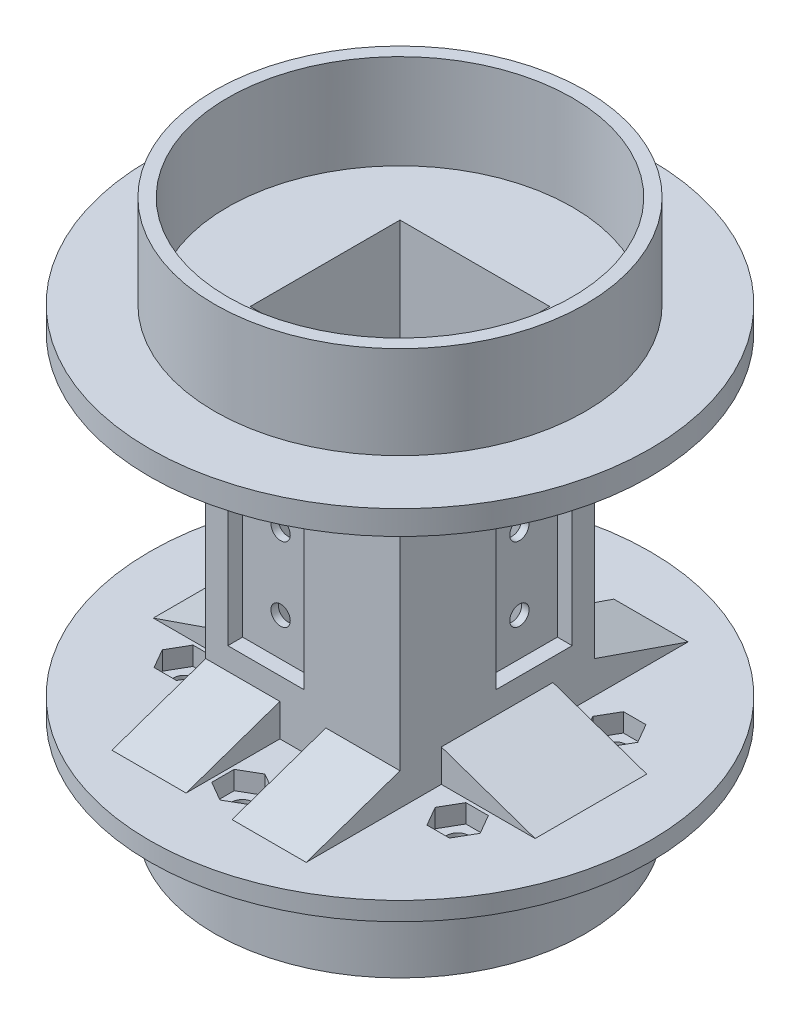
SolidWorks part; units mm, degrees
other "Markup1"
sketch "Sketch32" plane through (-67.5, -120, 67.5) normal (-0.5, 0, 0.866) x (0.866, 0, 0.5)
material "PLA"
ref_plane "Front Plane" through (0, 0, 0) normal (0, 0, 1) x (1, 0, 0)
ref_plane "Top Plane" through (0, 0, 0) normal (0, 1, 0) x (1, 0, 0)
ref_plane "Right Plane" through (0, 0, 0) normal (1, 0, 0) x (0, 0, -1)
sketch "Sketch1" plane through (0, 0, 0) normal (0, 1, 0) x (1, 0, 0)
  circle A0 centre (0, 0) radius 51.5
  circle A1 centre (0, 0) radius 46.5
  dimension "D1" = 103
  dimension "D2" = 93
extrude "Boss-Extrude1" add sketch "Sketch1" along normal blind 41
sketch "Sketch2" plane through (0, 0, 0) normal (0, -1, 0) x (1, 0, 0)
  circle A0 centre (0, 0) radius 46.5
  circle A1 centre (0, 0) radius 75
  dimension "D1" = 150
extrude "Boss-Extrude2" add sketch "Sketch2" along normal blind 5
sketch "Sketch3" plane through (0, -5, 0) normal (0, -1, 0) x (1, 0, 0)
  line L5 (-20.2, -20.2) -> (20.2, 20.2) construction
  line L6 (-20.2, 20.2) -> (20.2, -20.2) construction
  circle A0 centre (0, 0) radius 46.5
  point P0 (0, 0)
  dimension "D1" = 40.4
  dimension "D2" = 40.4
extrude "Boss-Extrude3" add sketch "Sketch3" against normal up to surface (5 mm away) up to face at (0, 0, 51.5)
sketch "Sketch4" plane through (0, 0, 0) normal (0, 1, 0) x (1, 0, 0)
  line L1 (-20.2, -20.2) -> (20.2, -20.2)
  line L2 (-20.2, -20.2) -> (-20.2, 20.2)
  line L3 (-20.2, 20.2) -> (20.2, 20.2)
  line L4 (20.2, -20.2) -> (20.2, 20.2)
  line L5 (-20.2, -20.2) -> (20.2, 20.2) construction
  line L6 (-20.2, 20.2) -> (20.2, -20.2) construction
  point P0 (0, 0)
  dimension "D1" = 40.4
  dimension "D2" = 40.4
extrude "Cut-Extrude1" cut sketch "Sketch4" against normal blind 6
sketch "Sketch5" plane through (0, -5, 0) normal (0, -1, 0) x (1, 0, 0)
  line L1 (-20.2, -20.2) -> (20.2, -20.2)
  line L2 (-20.2, -20.2) -> (-20.2, 20.2)
  line L3 (-20.2, 20.2) -> (20.2, 20.2)
  line L4 (20.2, -20.2) -> (20.2, 20.2)
  line L5 (-20.2, -20.2) -> (20.2, 20.2) construction
  line L6 (-20.2, 20.2) -> (20.2, -20.2) construction
  line L7 (-26.2, -26.2) -> (26.2, -26.2)
  line L8 (-26.2, -26.2) -> (-26.2, 26.2)
  line L9 (-26.2, 26.2) -> (26.2, 26.2)
  line L10 (26.2, -26.2) -> (26.2, 26.2)
  line L11 (-26.2, -26.2) -> (26.2, 26.2) construction
  line L12 (-26.2, 26.2) -> (26.2, -26.2) construction
  point P0 (0, 0)
  point P7 (0, 0)
  point P12 (-20.2, 0)
  point P13 (-26.2, 0)
  dimension "D1" = 6
  dimension "D2" = 6
extrude "Boss-Extrude4" add sketch "Sketch5" along normal blind 80
sketch "Sketch8" plane through (0, -85, 0) normal (0, -1, 0) x (1, 0, 0)
  line L1 (-26.2, -26.2) -> (26.2, -26.2)
  line L2 (-26.2, -26.2) -> (-26.2, 26.2)
  line L3 (-26.2, 26.2) -> (26.2, 26.2)
  line L4 (26.2, -26.2) -> (26.2, 26.2)
  line L5 (-26.2, -26.2) -> (26.2, 26.2) construction
  line L6 (-26.2, 26.2) -> (26.2, -26.2) construction
  point P0 (0, 0)
extrude "Boss-Extrude5" add sketch "Sketch8" along normal blind 5
sketch "Sketch9" plane through (0, 0, 0) normal (0, 1, 0) x (1, 0, 0)
  circle A0 centre (0, 0) radius 75
  circle A1 centre (0, 0) radius 51.5
extrude "Cut-Extrude4" cut sketch "Sketch9" against normal blind 1
sketch "Sketch10" plane through (0, -5, 0) normal (0, -1, 0) x (1, 0, 0)
  line L1 (-26.2, -26.2) -> (26.2, -26.2)
  line L2 (-26.2, -26.2) -> (-26.2, 26.2)
  line L3 (-26.2, 26.2) -> (26.2, 26.2)
  line L4 (26.2, -26.2) -> (26.2, 26.2)
  line L5 (-26.2, -26.2) -> (26.2, 26.2) construction
  line L6 (-26.2, 26.2) -> (26.2, -26.2) construction
  circle A0 centre (0, 0) radius 75
extrude "Boss-Extrude6" add sketch "Sketch10" along normal blind 1
sketch "Sketch11" plane through (0, 41, 0) normal (0, 1, 0) x (1, 0, 0)
  circle A0 centre (0, 0) radius 46.5
  circle A1 centre (0, 0) radius 51.5
extrude "Cut-Extrude5" cut sketch "Sketch11" against normal blind 13 and the other way through all
sketch "Sketch12" plane through (0, -85, 0) normal (0, 1, 0) x (1, 0, 0)
  line L1 (-20.2, -20.2) -> (20.2, -20.2)
  line L2 (-20.2, -20.2) -> (-20.2, 20.2)
  line L3 (-20.2, 20.2) -> (20.2, 20.2)
  line L4 (20.2, -20.2) -> (20.2, 20.2)
  line L5 (-20.2, -20.2) -> (20.2, 20.2) construction
  line L6 (-20.2, 20.2) -> (20.2, -20.2) construction
  point P0 (0, 0)
extrude "Cut-Extrude6" cut sketch "Sketch12" against normal blind 1
sketch "Sketch13" plane through (0, -90, 0) normal (0, -1, 0) x (1, 0, 0)
  line L1 (-26.2, -26.2) -> (26.2, -26.2)
  line L2 (-26.2, -26.2) -> (-26.2, 26.2)
  line L3 (-26.2, 26.2) -> (26.2, 26.2)
  line L4 (26.2, -26.2) -> (26.2, 26.2)
  line L5 (-26.2, -26.2) -> (26.2, 26.2) construction
  line L6 (-26.2, 26.2) -> (26.2, -26.2) construction
  point P0 (0, 0)
extrude "Boss-Extrude7" add sketch "Sketch13" along normal blind 1
sketch "Sketch6" plane through (0, 0, 26.2) normal (0, 0, 1) x (1, 0, 0)
  line L0 (-10, -6) -> (-10, -86) construction
  line L3 (26.2, -6) -> (-26.2, -6) construction
  line L4 (-20.25, -76.25) -> (0.25, -76.25)
  line L5 (-20.25, -76.25) -> (-20.25, -15.75)
  line L6 (-20.25, -15.75) -> (0.25, -15.75)
  line L7 (0.25, -76.25) -> (0.25, -15.75)
  line L8 (-20.25, -76.25) -> (0.25, -15.75) construction
  line L9 (-20.25, -15.75) -> (0.25, -76.25) construction
  line L10 (-26.2, -91) -> (-26.2, -6) construction
  point P6 (-10, -46)
  dimension "D1" = 20.5
  dimension "D2" = 60.5
  dimension "D3" = 9.75
  dimension "D4" = 5.95
extrude "Cut-Extrude2" cut sketch "Sketch6" against normal blind 4
sketch "Sketch7" plane through (0, 0, 22.2) normal (0, 0, 1) x (1, 0, 0)
  line L0 (0.25, -15.75) -> (-20.25, -15.75) construction
  circle A0 centre (-10, -26) radius 2.6
  circle A1 centre (-10, -46) radius 2.6
  circle A2 centre (-10, -66) radius 2.6
  point P10 (-10, -15.75)
  dimension "D1" = 5.2
  dimension "D2" = 5.2
  dimension "D3" = 5.2
  dimension "D4" = 10.25
  dimension "D5" = 20
  dimension "D6" = 20
  dimension "D7" = 0
extrude "Cut-Extrude3" cut sketch "Sketch7" against normal blind 2
sketch "Sketch14" plane through (-26.2, 0, 0) normal (-1, 0, 0) x (0, 0, 1)
  line L0 (26.2, -6) -> (-26.2, -6) construction
  line L1 (-0.25, -76.25) -> (20.25, -76.25)
  line L2 (-0.25, -76.25) -> (-0.25, -15.75)
  line L3 (-0.25, -15.75) -> (20.25, -15.75)
  line L4 (20.25, -76.25) -> (20.25, -15.75)
  line L5 (-0.25, -76.25) -> (20.25, -15.75) construction
  line L6 (-0.25, -15.75) -> (20.25, -76.25) construction
  line L7 (26.2, -91) -> (26.2, -6) construction
  point P0 (10, -46)
  dimension "D1" = 20.5
  dimension "D2" = 60.5
  dimension "D3" = 9.75
  dimension "D4" = 5.95
extrude "Cut-Extrude7" cut sketch "Sketch14" against normal blind 4
sketch "Sketch15" plane through (-22.2, 0, 0) normal (-1, 0, 0) x (0, 0, 1)
  line L0 (20.25, -15.75) -> (-0.25, -15.75) construction
  line L1 (-0.25, -15.75) -> (-0.25, -76.25) construction
  circle A0 centre (10, -26) radius 2.6
  circle A1 centre (10, -46) radius 2.6
  circle A2 centre (10, -66) radius 2.6
  dimension "D1" = 5.2
  dimension "D2" = 5.2
  dimension "D3" = 5.2
  dimension "D4" = 10.25
  dimension "D5" = 20
  dimension "D6" = 20
  dimension "D7" = 10.25
extrude "Cut-Extrude8" cut sketch "Sketch15" against normal blind 4
pattern_circular "CirPattern1" count 2 over 360 about axis through (0, 0, 0) along (0, 1, 0) of "Cut-Extrude2", "Cut-Extrude3"
pattern_circular "CirPattern2" count 2 over 360 about axis through (0, 0, 0) along (0, 1, 0) of "Cut-Extrude7", "Cut-Extrude8"
sketch "Sketch16" plane through (0, -1, 0) normal (0, 1, 0) x (1, 0, 0)
  circle A0 centre (0, 0) radius 75
  circle A1 centre (0, 0) radius 67.5
  dimension "D1" = 135
extrude "Cut-Extrude9" cut sketch "Sketch16" against normal blind 14
sketch "Sketch17" plane through (0, -91, 0) normal (0, -1, 0) x (1, 0, 0)
  circle A0 centre (0, 0) radius 67.5
extrude "Boss-Extrude8" add sketch "Sketch17" along normal blind 5
sketch "Sketch19" plane through (-26.2, 0, 0) normal (-1, 0, 0) x (0, 0, 1)
  line L0 (-26.2, -14.75) -> (26.2, -14.75) construction
  line L1 (-26.2, -91) -> (-26.2, -6) construction
  line L2 (26.2, -91) -> (26.2, -6) construction
  line L3 (20.25, -15.75) -> (-0.25, -15.75) construction
  line L4 (26.2, -14.75) -> (51.5, -6)
  line L5 (-67.5, -6) -> (67.5, -6) construction
  line L7 (26.2, -14.75) -> (26.2, -6)
  line L8 (26.2, -6) -> (51.5, -6)
  point P14 (51.5, -1)
  dimension "D1" = 1
extrude "Boss-Extrude9" add sketch "Sketch19" against normal up to surface (52.4 mm away) up to face at (26.2, -46, -10)
sketch "Sketch20" plane through (0, 0, 26.2) normal (0, 0, 1) x (1, 0, 0)
  line L0 (-26.2, -14.75) -> (26.2, -14.75) construction
  line L1 (-26.2, -14.75) -> (-26.2, -6) construction
  line L2 (26.2, -6) -> (26.2, -14.75) construction
  line L4 (0.25, -15.75) -> (-20.25, -15.75) construction
  line L5 (-26.2, -14.75) -> (-51.5, -6)
  line L6 (-67.5, -6) -> (67.5, -6) construction
  line L7 (-51.5, -6) -> (-26.2, -6)
  line L8 (-26.2, -6) -> (-26.2, -14.75)
  point P0 (-51.5, -1)
  dimension "D1" = 1
extrude "Boss-Extrude10" add sketch "Sketch20" against normal up to surface (52.4 mm away) up to face at (10, -46, -26.2)
sketch "Sketch21" plane through (-26.2, 0, 0) normal (-1, 0, 0) x (0, 0, 1)
  line L0 (-26.2, -14.75) -> (-51.5, -6)
  line L1 (-67.5, -6) -> (67.5, -6) construction
  line L2 (-51.5, -6) -> (-26.2, -6)
  line L3 (-26.2, -6) -> (-26.2, -14.75)
  point P0 (-51.5, -1)
extrude "Boss-Extrude11" add sketch "Sketch21" against normal up to surface (52.4 mm away) up to face at (26.2, -46, -10)
sketch "Sketch22" plane through (0, 0, -26.2) normal (0, 0, -1) x (-1, 0, 0)
  line L0 (-26.2, -14.75) -> (-51.5, -6)
  line L1 (-67.5, -6) -> (67.5, -6) construction
  line L2 (-51.5, -6) -> (-26.2, -6)
  line L3 (-26.2, -6) -> (-26.2, -14.75)
  point P0 (-51.5, -1)
extrude "Boss-Extrude12" add sketch "Sketch22" against normal up to surface (52.4 mm away) up to face at (-10, -46, 26.2)
sketch "Sketch23" plane through (26.2, 0, 0) normal (1, 0, 0) x (0, 0, -1)
  line L0 (67.5, -91) -> (-67.5, -91) construction
  line L1 (-26.2, -91) -> (-26.2, -14.75) construction
  line L2 (-51.5, -91) -> (-26.2, -82.25)
  line L3 (-26.2, -82.25) -> (-26.2, -91)
  line L4 (-26.2, -91) -> (-51.5, -91)
  point P0 (-51.5, -91)
  point P1 (-26.2, -82.25)
  point P11 (-51.5, -6)
  dimension "D1" = 8.75
sketch "Sketch24" plane through (0, 0, 26.2) normal (0, 0, 1) x (1, 0, 0)
  line L0 (-26.2, -82.25) -> (-51.5, -91)
  line L1 (67.5, -91) -> (-67.5, -91) construction
  line L2 (-51.5, -91) -> (-26.2, -91)
  line L3 (-26.2, -91) -> (-26.2, -82.25)
  point P0 (-51.5, -6)
sketch "Sketch25" plane through (-26.2, 0, 0) normal (-1, 0, 0) x (0, 0, 1)
  line L0 (-26.2, -82.25) -> (-51.5, -91)
  line L1 (67.5, -91) -> (-67.5, -91) construction
  line L2 (-51.5, -91) -> (-26.2, -91)
  line L3 (-26.2, -91) -> (-26.2, -82.25)
  point P0 (-51.5, -6)
sketch "Sketch26" plane through (0, 0, -26.2) normal (0, 0, -1) x (-1, 0, 0)
  line L0 (-26.2, -82.25) -> (-51.5, -91)
  line L1 (67.5, -91) -> (-67.5, -91) construction
  line L2 (-51.5, -91) -> (-26.2, -91)
  line L3 (-26.2, -91) -> (-26.2, -82.25)
  point P0 (-51.5, -6)
sketch "Sketch27" plane through (0, -86, 0) normal (0, 1, 0) x (1, 0, 0)
  line L0 (12.6, 22.2) -> (7.4, 22.2) construction
  line L1 (12.6, 22.2) -> (7.4, 22.2)
  line L2 (4.5, 20.2) -> (15.5, 20.2)
  line L3 (20.2, 20.2) -> (-20.2, 20.2) construction
  line L4 (-22.2, -7.4) -> (-22.2, -12.6) construction
  line L5 (-12.6, -22.2) -> (-7.4, -22.2) construction
  line L6 (22.2, 7.4) -> (22.2, 12.6) construction
  line L7 (-22.2, -7.4) -> (-22.2, -12.6)
  line L8 (-12.6, -22.2) -> (-7.4, -22.2)
  line L9 (22.2, 7.4) -> (22.2, 12.6)
  line L10 (20.2, 4.5) -> (20.2, 15.5)
  line L11 (20.2, -20.2) -> (20.2, 20.2) construction
  line L12 (-20.2, -15.5) -> (-20.2, -4.5)
  line L13 (4.5, 20.2) -> (15.5, 20.2)
  line L14 (4.5, 20.2) -> (4.5, 16.2)
  line L15 (4.5, 16.2) -> (15.5, 16.2)
  line L16 (15.5, 20.2) -> (15.5, 16.2)
  line L17 (20.2, 15.5) -> (16.2, 15.5)
  line L18 (20.2, 15.5) -> (20.2, 4.5)
  line L19 (20.2, 4.5) -> (16.2, 4.5)
  line L20 (16.2, 15.5) -> (16.2, 4.5)
  line L22 (-20.2, 20.2) -> (-20.2, -20.2) construction
  line L23 (-15.5, -20.2) -> (-4.5, -20.2)
  line L24 (-20.2, -15.5) -> (-16.2, -15.5)
  line L25 (-20.2, -15.5) -> (-20.2, -4.5)
  line L26 (-20.2, -4.5) -> (-16.2, -4.5)
  line L27 (-16.2, -15.5) -> (-16.2, -4.5)
  line L30 (-15.5, -20.2) -> (-4.5, -20.2)
  line L31 (-15.5, -20.2) -> (-15.5, -16.2)
  line L32 (-15.5, -16.2) -> (-4.5, -16.2)
  line L33 (-4.5, -20.2) -> (-4.5, -16.2)
  point P2 (22.2, 10)
  point P7 (10, 20.2)
  point P8 (10, 22.2)
  point P20 (20.2, 10)
  point P24 (-22.2, -10)
  point P27 (-20.2, -10)
  point P28 (-10, -22.2)
  point P37 (-10, -20.2)
  line M9 (20.2, -20.2) -> (20.2, 20.2)
  line M10 (20.2, 20.2) -> (-20.2, 20.2)
  line M11 (-20.2, 20.2) -> (-20.2, -20.2)
  line M12 (-20.2, -20.2) -> (20.2, -20.2)
  dimension "D1" = 11
  dimension "D2" = 11
  dimension "D3" = 4
  dimension "D4" = 4
  dimension "D5" = 11
  dimension "D6" = 4
  dimension "D7" = 11
  dimension "D8" = 4
extrude "Cut-Extrude10" cut sketch "Sketch27" against normal blind 20 contours L16 L14 L15 M10 | L17 L20 L19 M9 | L24 L27 L26 M11 | L33 L32 L31 M12
sketch "Sketch28" plane through (0, 28, 0) normal (0, 1, 0) x (1, 0, 0)
  circle A0 centre (0, 0) radius 50
  circle A1 centre (0, 0) radius 51.5
  dimension "D1" = 100
extrude "Cut-Extrude11" cut sketch "Sketch28" against normal up to surface (29 mm away) up to face at (0, -1, 51.5)
sketch "Sketch29" plane through (0, -96, 0) normal (0, -1, 0) x (1, 0, 0)
  circle A0 centre (0, 0) radius 50
  circle A1 centre (0, 0) radius 45
  dimension "D1" = 100
  dimension "D2" = 90
extrude "Boss-Extrude17" add sketch "Sketch29" along normal blind 24
sketch "Sketch30" plane through (0, -96, 0) normal (0, -1, 0) x (1, 0, 0)
  line L0 (0.25, 22.2) -> (0.25, 26.2) construction
  line L1 (-20.25, 22.2) -> (-20.25, 26.2) construction
  line L2 (0.25, 22.2) -> (0.25, 26.2)
  line L3 (-20.25, 22.2) -> (-20.25, 26.2)
  line L4 (-20.25, 22.2) -> (0.25, 22.2) construction
  line L5 (-4.5, 20.2) -> (-15.5, 20.2) construction
  line L6 (-15.75, 15.95) -> (-4.25, 15.95)
  line L7 (-15.75, 15.95) -> (-15.75, 20.45)
  line L8 (-15.75, 20.45) -> (-4.25, 20.45)
  line L9 (-4.25, 15.95) -> (-4.25, 20.45)
  line L10 (-15.75, 15.95) -> (-4.25, 20.45) construction
  line L11 (-15.75, 20.45) -> (-4.25, 15.95) construction
  line L12 (-15.5, 16.2) -> (-15.5, 20.2) construction
  line L13 (-20.2, 15.5) -> (-20.2, 4.5) construction
  line L14 (-20.45, 4.25) -> (-15.95, 4.25)
  line L15 (-20.45, 4.25) -> (-20.45, 15.75)
  line L16 (-20.45, 15.75) -> (-15.95, 15.75)
  line L17 (-15.95, 4.25) -> (-15.95, 15.75)
  line L18 (-20.45, 4.25) -> (-15.95, 15.75) construction
  line L19 (-20.45, 15.75) -> (-15.95, 4.25) construction
  line L20 (-16.2, 4.5) -> (-20.2, 4.5) construction
  point P4 (-10, 18.2)
  point P13 (-18.2, 10)
  line M12 (-15.5, 20.2) -> (-4.5, 20.2)
  line M13 (-4.5, 20.2) -> (-4.5, 16.2)
  line M14 (-4.5, 16.2) -> (-15.5, 16.2)
  line M15 (-15.5, 16.2) -> (-15.5, 20.2)
  line M16 (-20.2, 15.5) -> (-16.2, 15.5)
  line M17 (-16.2, 15.5) -> (-16.2, 4.5)
  line M18 (-16.2, 4.5) -> (-20.2, 4.5)
  line M19 (-20.2, 4.5) -> (-20.2, 15.5)
  dimension "D1" = 4.5
  dimension "D2" = 0.25
  dimension "D3" = 11.5
  dimension "D4" = 0.25
  dimension "D5" = 4.5
  dimension "D6" = 0.25
  dimension "D7" = 0.25
  dimension "D8" = 11.5
extrude "Cut-Extrude12" cut sketch "Sketch30" against normal blind 10 contours M16 M19 M18 M17 | M12 M15 M14 M13 | L6 L9 L8 L7 M15 M12 M13 M14 | L14 L17 L16 L15 M19 M16 M17 M18
sketch "Sketch31" plane through (0, -96, 0) normal (0, -1, 0) x (1, 0, 0)
  line L0 (16.2, -15.5) -> (20.2, -15.5) construction
  line L1 (15.95, -15.75) -> (20.45, -15.75)
  line L2 (15.95, -15.75) -> (15.95, -4.25)
  line L3 (15.95, -4.25) -> (20.45, -4.25)
  line L4 (20.45, -15.75) -> (20.45, -4.25)
  line L5 (15.95, -15.75) -> (20.45, -4.25) construction
  line L6 (15.95, -4.25) -> (20.45, -15.75) construction
  line L7 (4.25, -20.45) -> (15.75, -20.45)
  line L8 (4.25, -20.45) -> (4.25, -15.95)
  line L9 (4.25, -15.95) -> (15.75, -15.95)
  line L10 (15.75, -20.45) -> (15.75, -15.95)
  line L11 (4.25, -20.45) -> (15.75, -15.95) construction
  line L12 (4.25, -15.95) -> (15.75, -20.45) construction
  line L13 (20.2, -15.5) -> (20.2, -4.5) construction
  line L14 (4.5, -16.2) -> (4.5, -20.2) construction
  line L15 (15.5, -16.2) -> (4.5, -16.2) construction
  point P0 (18.2, -10)
  point P5 (10, -18.2)
  dimension "D1" = 4.5
  dimension "D2" = 11.5
  dimension "D3" = 4.5
  dimension "D4" = 11.5
  dimension "D5" = 0.25
  dimension "D6" = 0.25
  dimension "D7" = 0.25
  dimension "D8" = 0.25
extrude "Cut-Extrude13" cut sketch "Sketch31" against normal blind 10
sketch "Sketch33" plane through (0, -96, 0) normal (0, -1, 0) x (1, 0, 0)
  circle A0 centre (0, 0) radius 35
  circle A1 centre (0, 0) radius 45
  dimension "D1" = 70
extrude "Boss-Extrude18" add sketch "Sketch33" along normal up to surface (24 mm away) up to face at (0, -120, -50)
sketch "Sketch34" plane through (0, -120, 0) normal (0, -1, 0) x (1, 0, 0)
  circle A0 centre (0, 0) radius 35
  circle A1 centre (0, 0) radius 50
extrude "Boss-Extrude19" add sketch "Sketch34" along normal blind 1.5
sketch "Sketch35" plane through (0, -121.5, 0) normal (0, -1, 0) x (1, 0, 0)
  circle A0 centre (0, 0) radius 42.5
  circle A1 centre (0, 42.5) radius 2.95
  circle A2 centre (36.8061, 21.25) radius 2.95
  circle A3 centre (36.8061, -21.25) radius 2.95
  circle A4 centre (0, -42.5) radius 2.95
  circle A5 centre (-36.8061, -21.25) radius 2.95
  circle A6 centre (-36.8061, 21.25) radius 2.95
  point P17 (0, 0)
  dimension "D1" = 85
  dimension "D2" = 5.9
  dimension "D3" = 6
extrude "Cut-Extrude14" cut sketch "Sketch35" against normal blind 45 contours A0 A1 | A0 A1 | A2 | A3 | A4 | A5 | A6
extrude "Boss-Extrude20" add sketch "Sketch25" against normal blind 20
sketch "Sketch37" plane through (26.2, 0, 0) normal (1, 0, 0) x (0, 0, -1)
  line L3 (26.2, -82.25) -> (26.2, -91)
  line L4 (26.2, -91) -> (51.5, -91)
  line L5 (51.5, -91) -> (26.2, -82.25)
  line L6 (26.2, -82.25) -> (26.2, -91)
  line L7 (26.2, -91) -> (51.5, -91)
  line L8 (51.5, -91) -> (26.2, -82.25)
  dimension "D1" = 0
extrude "Boss-Extrude21" add sketch "Sketch37" against normal blind 20
ref_plane "Plane1" through (0, 0, 0) normal (0, 0, -1) x (-1, 0, 0)
sketch "Sketch39" plane through (0, 0, 0) normal (0, 0, -1) x (-1, 0, 0)
  line L0 (-51.5, -91) -> (-26.2, -91) construction
  line L1 (-26.2, -91) -> (-26.2, -82.25) construction
  line L2 (-26.2, -82.25) -> (-51.5, -91) construction
  line L3 (-51.5, -91) -> (-26.2, -91)
  line L4 (-26.2, -91) -> (-26.2, -82.25)
  line L5 (-26.2, -82.25) -> (-51.5, -91)
extrude "Boss-Extrude22" add sketch "Sketch39" along normal mid plane 30.1
extrude "Boss-Extrude23" add sketch "Sketch23" against normal blind 20
sketch "Sketch40" plane through (-26.2, 0, 0) normal (-1, 0, 0) x (0, 0, 1)
  line L3 (26.2, -91) -> (51.5, -91)
  line L4 (51.5, -91) -> (26.2, -82.25)
  line L5 (26.2, -82.25) -> (26.2, -91)
  line L6 (26.2, -91) -> (51.5, -91)
  line L7 (51.5, -91) -> (26.2, -82.25)
  line L8 (26.2, -82.25) -> (26.2, -91)
  dimension "D1" = 0
extrude "Boss-Extrude24" add sketch "Sketch40" against normal blind 20
ref_plane "Plane2" through (0, 0, 0) normal (0, 0, 1) x (1, 0, 0)
sketch "Sketch41" plane through (0, 0, 0) normal (0, 0, 1) x (1, 0, 0)
  line L0 (-51.5, -91) -> (-26.2, -91) construction
  line L1 (-26.2, -91) -> (-26.2, -82.25) construction
  line L2 (-26.2, -82.25) -> (-51.5, -91) construction
  line L3 (-51.5, -91) -> (-26.2, -91)
  line L4 (-26.2, -91) -> (-26.2, -82.25)
  line L5 (-26.2, -82.25) -> (-51.5, -91)
extrude "Boss-Extrude25" add sketch "Sketch41" along normal mid plane 30.1
sketch "Sketch38" plane through (0, -91, 0) normal (0, 1, 0) x (1, 0, 0)
  line L0 (6.2, 26.2) -> (26.2, 26.2) construction
  line L1 (39.8372, -16) -> (33.775, -16)
  line L2 (33.775, -16) -> (30.7439, -21.25)
  line L3 (30.7439, -21.25) -> (33.775, -26.5)
  line L4 (33.775, -26.5) -> (39.8372, -26.5)
  line L5 (39.8372, -26.5) -> (42.8683, -21.25)
  line L6 (42.8683, -21.25) -> (39.8372, -16)
  line L7 (39.8372, 26.5) -> (33.775, 26.5)
  line L8 (33.775, 26.5) -> (30.7439, 21.25)
  line L9 (30.7439, 21.25) -> (33.775, 16)
  line L10 (33.775, 16) -> (39.8372, 16)
  line L11 (39.8372, 16) -> (42.8683, 21.25)
  line L12 (42.8683, 21.25) -> (39.8372, 26.5)
  line L13 (26.2, -15.05) -> (47.6541, -15.05) construction
  line L14 (26.2, 51.5) -> (26.2, 15.05) construction
  line L15 (26.2, 15.05) -> (47.6541, 15.05) construction
  line L16 (6.2, -51.5) -> (6.2, -26.2) construction
  line L17 (5.25, -45.5311) -> (5.25, -39.4689)
  line L18 (5.25, -39.4689) -> (0, -36.4378)
  line L19 (0, -36.4378) -> (-5.25, -39.4689)
  line L20 (-5.25, -39.4689) -> (-5.25, -45.5311)
  line L21 (-5.25, -45.5311) -> (0, -48.5622)
  line L22 (0, -48.5622) -> (5.25, -45.5311)
  line L24 (-39.8372, -26.5) -> (-33.775, -26.5)
  line L25 (-33.775, -26.5) -> (-30.7439, -21.25)
  line L26 (-30.7439, -21.25) -> (-33.775, -16)
  line L27 (-33.775, -16) -> (-39.8372, -16)
  line L28 (-39.8372, -16) -> (-42.8683, -21.25)
  line L29 (-42.8683, -21.25) -> (-39.8372, -26.5)
  line L30 (-51.5, -15.05) -> (-26.2, -15.05) construction
  line L31 (-51.5, 15.05) -> (-26.2, 15.05) construction
  line L32 (-39.8372, 16) -> (-33.775, 16)
  line L33 (-33.775, 16) -> (-30.7439, 21.25)
  line L34 (-30.7439, 21.25) -> (-33.775, 26.5)
  line L35 (-33.775, 26.5) -> (-39.8372, 26.5)
  line L36 (-39.8372, 26.5) -> (-42.8683, 21.25)
  line L37 (-42.8683, 21.25) -> (-39.8372, 16)
  line L38 (-6.2, 51.5) -> (-6.2, 26.2) construction
  line L39 (0, 48.5622) -> (-5.25, 45.5311)
  line L40 (-5.25, 45.5311) -> (-5.25, 39.4689)
  line L41 (-5.25, 39.4689) -> (0, 36.4378)
  line L42 (0, 36.4378) -> (5.25, 39.4689)
  line L43 (5.25, 39.4689) -> (5.25, 45.5311)
  line L44 (5.25, 45.5311) -> (0, 48.5622)
  circle A0 centre (36.8061, -21.25) radius 5.25 construction
  circle A1 centre (36.8061, 21.25) radius 5.25 construction
  circle A2 centre (0, -42.5) radius 5.25 construction
  circle A3 centre (-36.8061, -21.25) radius 5.25 construction
  circle A4 centre (-36.8061, 21.25) radius 5.25 construction
  circle A5 centre (0, 42.5) radius 5.25 construction
  dimension "D1" = 10.5
  dimension "D2" = 10.5
  dimension "D3" = 0.95
  dimension "D4" = 0.95
  dimension "D5" = 10.5
  dimension "D6" = 10.5
  dimension "D7" = 10.5
  dimension "D8" = 10.5
extrude "Cut-Extrude15" cut sketch "Sketch38" against normal blind 5
sketch "Sketch42" plane through (0, 28, 0) normal (0, 1, 0) x (1, 0, 0)
  circle A0 centre (0, 0) radius 50
  circle A1 centre (0, 0) radius 46.5
extrude "Cut-Extrude16" cut sketch "Sketch42" against normal blind 4
sketch "Sketch43" plane through (0, -1, 0) normal (0, 1, 0) x (1, 0, 0)
  circle A0 centre (0, 0) radius 67.5
  circle A1 centre (0, 0) radius 50
extrude "Cut-Extrude17" cut sketch "Sketch43" against normal blind 0.5
sketch "Sketch44" plane through (0, -1.5, 0) normal (0, 1, 0) x (1, 0, 0)
  circle A0 centre (0, 0) radius 50
  circle A1 centre (0, 0) radius 67.5
extrude "Boss-Extrude26" add sketch "Sketch44" along normal blind 2
sketch "Sketch45" plane through (0, 24, 0) normal (0, 1, 0) x (1, 0, 0)
  circle A0 centre (0, 0) radius 46.5
  circle A1 centre (0, 0) radius 50
extrude "Boss-Extrude27" add sketch "Sketch45" along normal blind 1.5
sketch "Sketch46" plane through (0, -96, 0) normal (0, -1, 0) x (1, 0, 0)
  line L1 (-15.75, 15.95) -> (-4.25, 15.95)
  line L2 (-15.75, 15.95) -> (-15.75, 13.95)
  line L3 (-15.75, 13.95) -> (-4.25, 13.95)
  line L4 (-4.25, 15.95) -> (-4.25, 13.95)
  line L5 (-15.95, 4.25) -> (-13.95, 4.25)
  line L6 (-15.95, 4.25) -> (-15.95, 15.75)
  line L7 (-15.95, 15.75) -> (-13.95, 15.75)
  line L8 (-13.95, 4.25) -> (-13.95, 15.75)
  line L9 (15.75, -15.95) -> (4.25, -15.95)
  line L10 (15.75, -15.95) -> (15.75, -13.95)
  line L11 (15.75, -13.95) -> (4.25, -13.95)
  line L12 (4.25, -15.95) -> (4.25, -13.95)
  line L13 (15.95, -4.25) -> (13.95, -4.25)
  line L14 (15.95, -4.25) -> (15.95, -15.75)
  line L15 (15.95, -15.75) -> (13.95, -15.75)
  line L16 (13.95, -4.25) -> (13.95, -15.75)
  dimension "D1" = 2
  dimension "D2" = 2
  dimension "D3" = 2
  dimension "D4" = 2
extrude "Cut-Extrude18" cut sketch "Sketch46" against normal up to surface (10 mm away) contours L16 L15 L14 L13 | L11 L12 L9 L10 | L3 L4 L1 L2 | L8 L7 L6 L5 up to face at (0, -86, 0)
